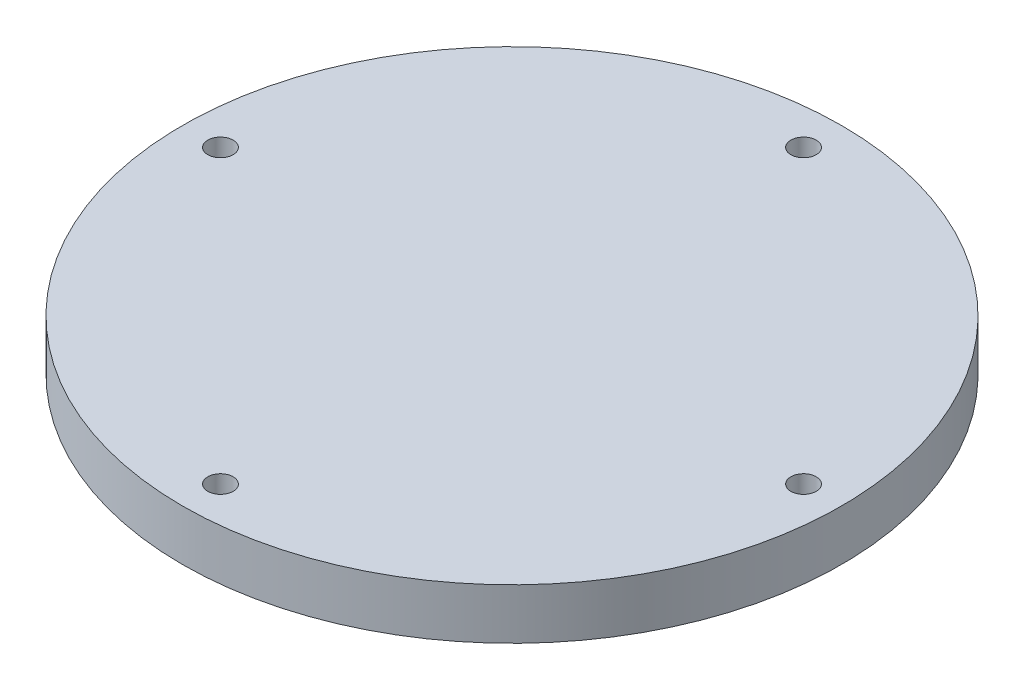
SolidWorks part; units mm, degrees
ref_plane "Front Plane" through (0, 0, 0) normal (0, 0, 1) x (1, 0, 0)
ref_plane "Top Plane" through (0, 0, 0) normal (0, 1, 0) x (1, 0, 0)
ref_plane "Right Plane" through (0, 0, 0) normal (1, 0, 0) x (0, 0, -1)
sketch "Sketch1" plane through (0, 0, 0) normal (0, 1, 0) x (1, 0, 0)
  circle A0 centre (0, 0) radius 65
  dimension "D1" = 130
extrude "Boss-Extrude1" add sketch "Sketch1" along normal blind 10
sketch "Sketch2" plane through (0, 10, 0) normal (0, 1, 0) x (1, 0, 0)
  circle A0 centre (0, 57.5) radius 2.5
  circle A1 centre (57.5, 0) radius 2.5
  circle A2 centre (0, -57.5) radius 2.5
  circle A3 centre (-57.5, 0) radius 2.5
  point P12 (0, 0)
  dimension "D2" = 5
  dimension "D1" = 4
extrude "Cut-Extrude1" cut sketch "Sketch2" against normal through all
